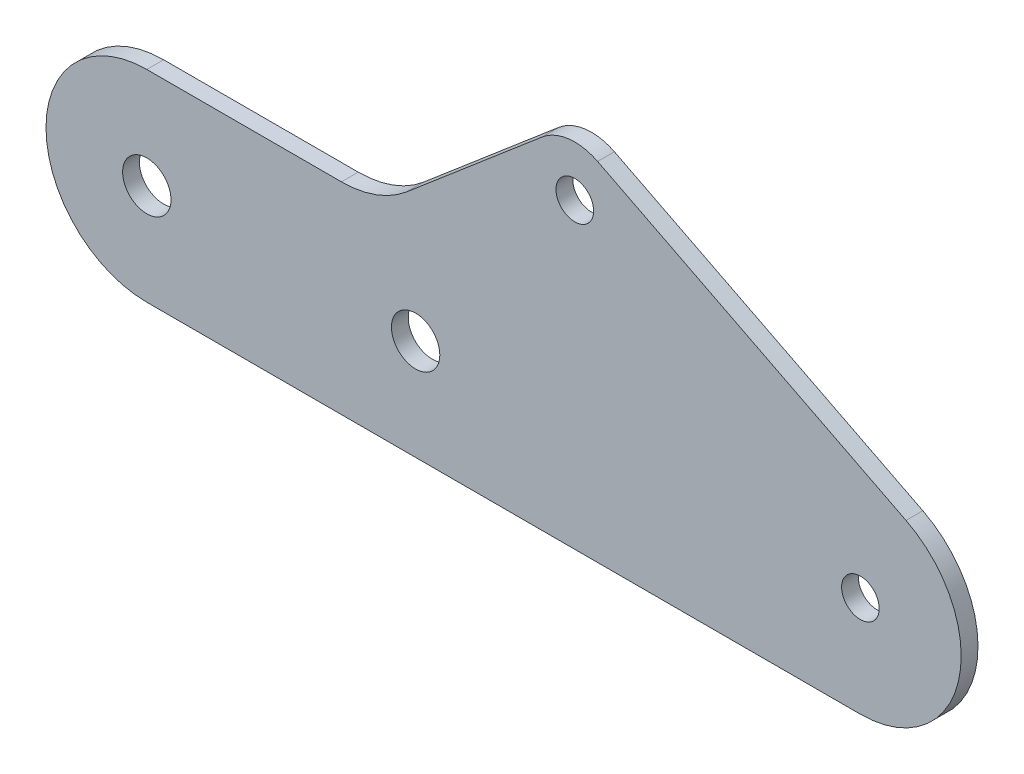
SolidWorks part; units mm, degrees
ref_plane "Front Plane" through (0, 0, 0) normal (0, 0, 1) x (1, 0, 0)
ref_plane "Top Plane" through (0, 0, 0) normal (0, 1, 0) x (1, 0, 0)
ref_plane "Right Plane" through (0, 0, 0) normal (1, 0, 0) x (0, 0, -1)
sketch "Sketch1" plane through (0, 0, 0) normal (0, 0, 1) x (1, 0, 0)
  line L1 (-3.9295, -9.525) -> (38.1, -9.525)
  line L2 (-4.7646, 11.7953) -> (8.0265, 22.6774)
  line L3 (42.4136, 8.4922) -> (13.2693, 23.2961)
  line L4 (-29.3295, 9.525) -> (-10.9366, 9.525)
  line L5 (-29.3295, -9.525) -> (-3.9295, -9.525)
  line L6 (-4.7646, 11.7953) -> (-14.9402, 3.1382) construction
  circle A1 centre (-3.9295, 0) radius 2.286
  circle A2 centre (38.1, 0) radius 1.778
  arc A3 (38.1, -9.525) -> (42.4136, 8.4922) centre (38.1, 0) ccw
  arc A4 (13.2693, 23.2961) -> (8.0265, 22.6774) centre (11.1125, 19.05) ccw
  circle A5 centre (11.1125, 19.05) radius 1.778
  circle A6 centre (-29.3295, 0) radius 2.286
  arc A7 (-29.3295, 9.525) -> (-29.3295, -9.525) centre (-29.3295, 0) ccw
  arc A8 (-10.9366, 9.525) -> (-4.7646, 11.7953) centre (-10.9366, 19.05) ccw
  point P23 (-14.9402, 3.1382)
  dimension "D1" = 9.525
  dimension "D2" = 4.572
  dimension "D4" = 19.05
  dimension "D3" = 9.525
  dimension "D7" = 3.556
  dimension "D8" = 19.05
  dimension "D5" = 26.9875
  dimension "D6" = 19.05
  dimension "D9" = 9.525
extrude "Boss-Extrude1" add sketch "Sketch1" along normal blind 1.5875
